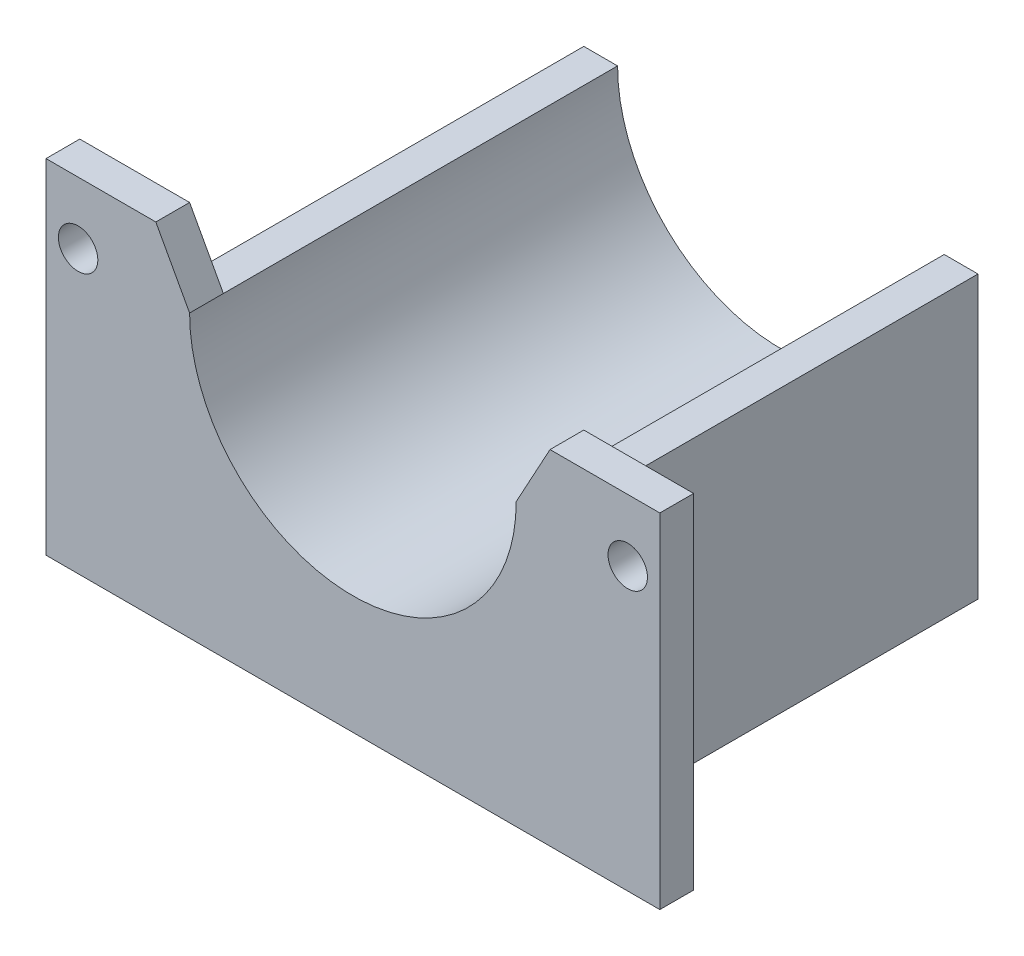
SolidWorks part; units mm, degrees
ref_plane "Спереди" through (0, 0, 0) normal (0, 0, 1) x (1, 0, 0)
ref_plane "Сверху" through (0, 0, 0) normal (0, 1, 0) x (1, 0, 0)
ref_plane "Справа" through (0, 0, 0) normal (1, 0, 0) x (0, 0, -1)
other "Configuration Table"
sketch "Эскиз1" plane through (0, 0, 0) normal (0, 0, 1) x (1, 0, 0)
  line L0 (-32, 0) -> (-35, 0)
  line L1 (0, 0) -> (-3, 0)
  line L2 (0, 0) -> (0, -25)
  line L3 (0, -25) -> (-35, -25)
  line L4 (-35, 0) -> (-35, -25)
  arc A0 (-32, 0) -> (-3, 0) centre (-17.5, 0) ccw
  dimension "D3" = 29
  dimension "D4" = 3
  dimension "D5" = 3
  dimension "D1" = 35
  dimension "D2" = 25
extrude "Бобышка-Вытянуть1" add sketch "Эскиз1" along normal blind 35
sketch "Эскиз2" plane through (0, 0, 35) normal (0, 0, 1) x (1, 0, 0)
  line L0 (-17.5, -14.5) -> (-17.5, -25) construction
  line L1 (-35, -25) -> (0, -25) construction
  line L2 (0, 0) -> (-3, 0) construction
  line L3 (-44.75, -25) -> (9.75, -25)
  line L4 (-44.75, -25) -> (-44.75, 5.5)
  line L5 (-44.75, 5.5) -> (9.75, 5.5)
  line L6 (9.75, -25) -> (9.75, 5.5)
  line L7 (-40.15, 0) -> (-40.15, 5.5) construction
  line L8 (5.15, 0) -> (5.15, 5.5) construction
  arc A0 (-32, 0) -> (-3, 0) centre (-17.5, 0) ccw construction
  circle A1 centre (6.9, 0) radius 1.75
  circle A2 centre (-41.9, 0) radius 1.75
  point P13 (-1.5, 0)
  point P22 (0, 0)
  dimension "D2" = 3.5
  dimension "D3" = 45.3
  dimension "D1" = 5.5
  dimension "54,5" = 54.5
extrude "Бобышка-Вытянуть2" add sketch "Эскиз2" along normal blind 3
sketch "Эскиз3" plane through (0, 0, 35) normal (0, 0, -1) x (-1, 0, 0)
  line L0 (0, 0) -> (35, 0) construction
  line L1 (17.5, -14.5) -> (17.5, 0) construction
  line L2 (3, 0) -> (0, 5.5)
  line L3 (-9.75, 5.5) -> (44.75, 5.5) construction
  line L4 (0, 5.5) -> (35, 5.5)
  line L5 (35, 5.5) -> (32, 0)
  arc A0 (3, 0) -> (32, 0) centre (17.5, 0) ccw
  arc A1 (3, 0) -> (32, 0) centre (17.5, 0) ccw construction
  point P12 (0, 0)
  point P19 (0, 0)
extrude "Вырез-Вытянуть2" cut sketch "Эскиз3" against normal through all
